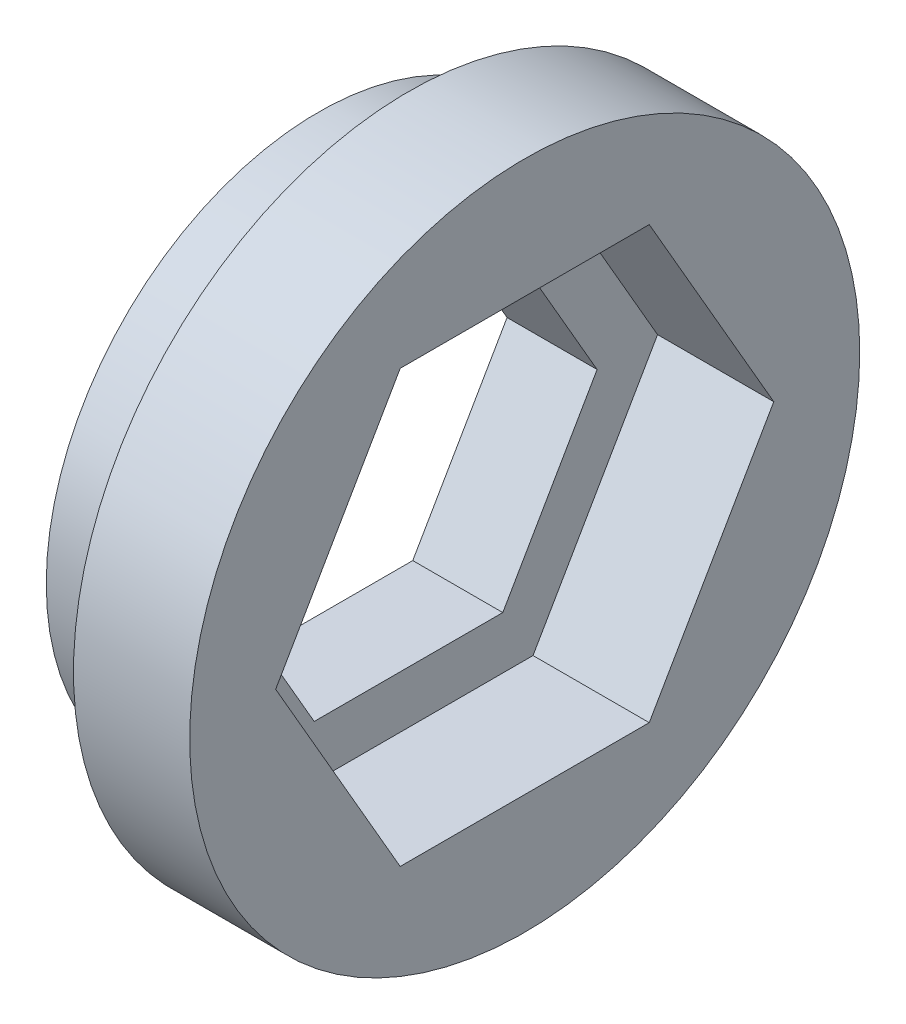
SolidWorks part; units mm, degrees
ref_plane "Front Plane" through (0, 0, 0) normal (0, 0, 1) x (1, 0, 0)
ref_plane "Top Plane" through (0, 0, 0) normal (0, 1, 0) x (1, 0, 0)
ref_plane "Right Plane" through (0, 0, 0) normal (1, 0, 0) x (0, 0, -1)
sketch "Sketch1" plane through (0, 0, 0) normal (1, 0, 0) x (0, 0, -1)
  line L1 (7.5523, 0) -> (3.7762, 6.5405)
  line L2 (3.7762, 6.5405) -> (-3.7762, 6.5405)
  line L3 (-3.7762, 6.5405) -> (-7.5523, 0)
  line L4 (-7.5523, 0) -> (-3.7762, -6.5405)
  line L5 (-3.7762, -6.5405) -> (3.7762, -6.5405)
  line L6 (3.7762, -6.5405) -> (7.5523, 0)
  circle A0 centre (0, 0) radius 6.5405 construction
  circle A1 centre (0, 0) radius 10.16
  dimension "D1" = 13.081
  dimension "D2" = 20.32
extrude "Boss-Extrude1" add sketch "Sketch1" along normal mid plane 3.5242
sketch "Sketch2" plane through (-1.7621, 0, 0) normal (-1, 0, 0) x (0, 0, 1)
  line L1 (5.7192, 0) -> (2.8596, 4.953)
  line L2 (2.8596, 4.953) -> (-2.8596, 4.953)
  line L3 (-2.8596, 4.953) -> (-5.7192, 0)
  line L4 (-5.7192, 0) -> (-2.8596, -4.953)
  line L5 (-2.8596, -4.953) -> (2.8596, -4.953)
  line L6 (2.8596, -4.953) -> (5.7192, 0)
  circle A0 centre (0, 0) radius 4.953 construction
  circle A1 centre (0, 0) radius 8.255
  dimension "D1" = 9.906
  dimension "D2" = 16.51
extrude "Boss-Extrude2" add sketch "Sketch2" along normal blind 2.7305
fillet "Fillet1" radius 1.27 1 edges at (-1.7621, 0, -8.255)
